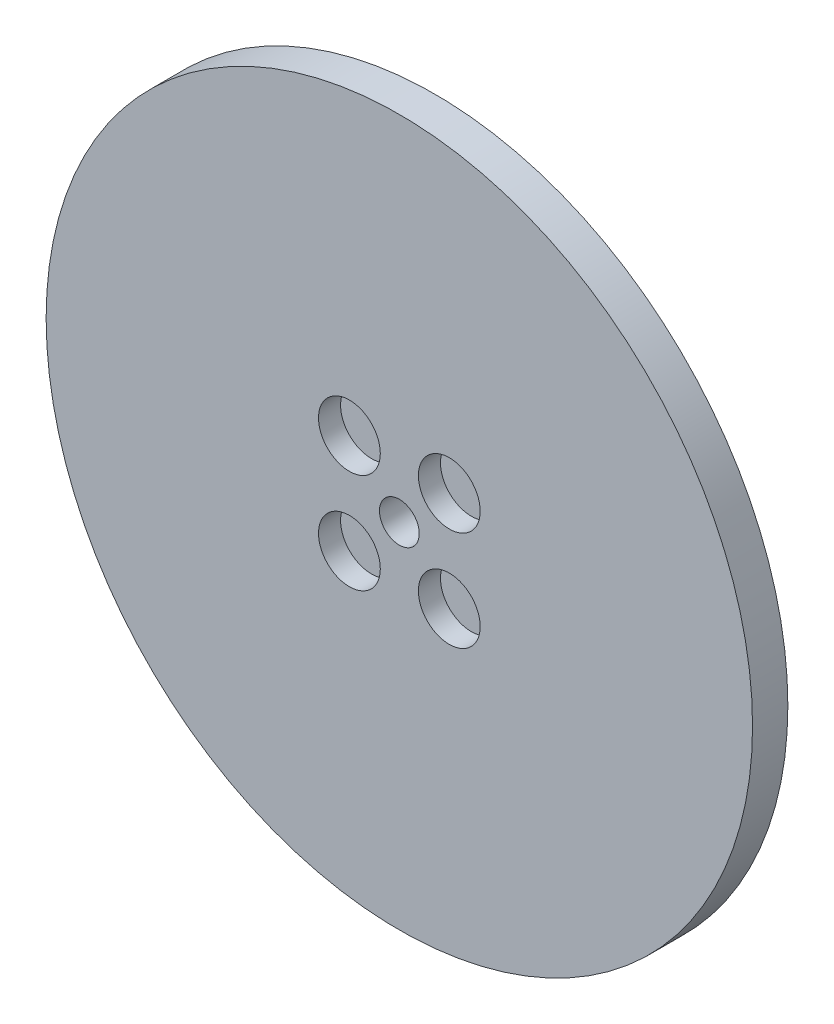
SolidWorks part; units mm, degrees
ref_plane "Front Plane" through (0, 0, 0) normal (0, 0, 1) x (1, 0, 0)
ref_plane "Top Plane" through (0, 0, 0) normal (0, 1, 0) x (1, 0, 0)
ref_plane "Right Plane" through (0, 0, 0) normal (1, 0, 0) x (0, 0, -1)
sketch "Sketch1" plane through (0, 0, 0) normal (0, 0, 1) x (1, 0, 0)
  circle A0 centre (0, 0) radius 12.5
  circle A1 centre (0, 0) radius 30
  dimension "D1" = 25
  dimension "D2" = 60
extrude "Boss-Extrude1" add sketch "Sketch1" along normal blind 4
sketch "Sketch2" plane through (0, 0, 4) normal (0, 0, 1) x (1, 0, 0)
  line L1 (-5.656, 5.6577) -> (5.656, 5.6577) construction
  line L2 (-5.656, 5.6577) -> (-5.656, -5.6577) construction
  line L3 (-5.656, -5.6577) -> (5.656, -5.6577) construction
  line L4 (5.656, 5.6577) -> (5.656, -5.6577) construction
  circle A0 centre (0, 0) radius 2.25
  circle A1 centre (-5.656, 5.6577) radius 1.5
  circle A2 centre (-5.656, -5.6577) radius 1.5
  circle A3 centre (5.656, -5.6577) radius 1.5
  circle A4 centre (5.656, 5.6577) radius 1.5
  circle A5 centre (0, 0) radius 40
  point P15 (0, -5.6577)
  point P16 (-5.656, 0)
  dimension "D1" = 4.5
  dimension "D4" = 3
  dimension "D5" = 80
  dimension "D2" = 16
  dimension "D3" = 11.3154
extrude "Boss-Extrude2" add sketch "Sketch2" along normal blind 4
sketch "Sketch3" plane through (0, 0, 8) normal (0, 0, 1) x (1, 0, 0)
  circle A0 centre (-5.656, 5.6577) radius 3.5
  circle A1 centre (5.656, 5.6577) radius 3.5
  circle A2 centre (5.656, -5.6577) radius 3.5
  circle A3 centre (-5.656, -5.6577) radius 3.5
  dimension "D1" = 7
extrude "Cut-Extrude1" cut sketch "Sketch3" against normal blind 2.5
sketch "Sketch4" plane through (0, 0, 0) normal (0, 0, -1) x (-1, 0, 0)
  circle A0 centre (-20, 0) radius 5.15
  circle A3 centre (0, 0) radius 20 construction
  point P2 (0, 0)
  point P3 (0, 0)
  dimension "D1" = 10.3
  dimension "D2" = 40
extrude "Cut-Extrude2" cut sketch "Sketch4" against normal blind 4
sketch "Sketch5" plane through (0, 0, 5.5) normal (0, 0, 1) x (1, 0, 0)
  circle A0 centre (-5.656, 5.6577) radius 3.5
  circle A1 centre (5.656, 5.6577) radius 3.5
  circle A2 centre (-5.656, -5.6577) radius 3.5
  circle A3 centre (5.656, -5.6577) radius 3.5
extrude "Boss-Extrude3" add sketch "Sketch5" against normal blind 0.2
